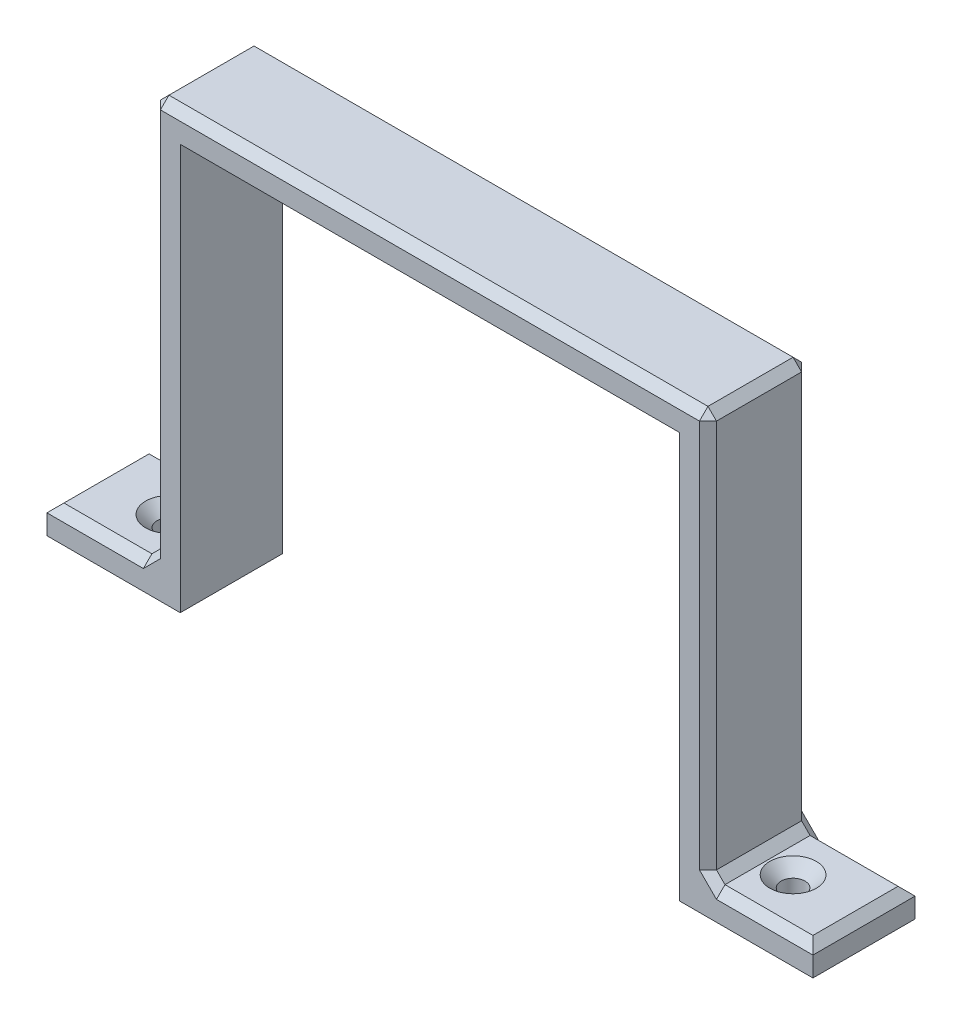
SolidWorks part; units mm, degrees
ref_plane "Front Plane" through (0, 0, 0) normal (0, 0, 1) x (1, 0, 0)
ref_plane "Top Plane" through (0, 0, 0) normal (0, 1, 0) x (1, 0, 0)
ref_plane "Right Plane" through (0, 0, 0) normal (1, 0, 0) x (0, 0, -1)
sketch "Sketch1" plane through (0, 0, 0) normal (0, 0, 1) x (1, 0, 0)
  line L0 (0, 48.7073) -> (0, -14.6895) construction
  line L1 (44, -27.85) -> (44, 43.65)
  line L2 (56.3161, -27.85) -> (55.25, -27.85) construction
  line L3 (44, 43.65) -> (-44, 43.65)
  line L4 (-49, 48.65) -> (49, 48.65)
  line L5 (49, 48.65) -> (49, -22.85)
  line L6 (49, -22.85) -> (67.5, -22.85)
  line L7 (67.5, -22.85) -> (67.5, -27.85)
  line L9 (67.5, -27.85) -> (44, -27.85)
  line L10 (49, -22.85) -> (49, -27.85) construction
  line L11 (0, 48.65) -> (0, 43.65) construction
  line L12 (-49, -22.85) -> (-49, -27.85) construction
  line L13 (-67.5, -27.85) -> (-44, -27.85)
  line L14 (-67.5, -22.85) -> (-67.5, -27.85)
  line L15 (-49, -22.85) -> (-67.5, -22.85)
  line L16 (-49, 48.65) -> (-49, -22.85)
  line L17 (-44, -27.85) -> (-44, 43.65)
  dimension "D1" = 71.5
  dimension "D2" = 44
  dimension "D3" = 5
  dimension "D4" = 5
  dimension "D5" = 135
  dimension "D6" = 5
extrude "Boss-Extrude1" add sketch "Sketch1" along normal mid plane 18
sketch "Sketch2" plane through (0, -27.85, 0) normal (0, -1, 0) x (1, 0, 0)
  line L0 (0, 8.47) -> (0, -7.1138) construction
  circle A0 centre (55, 0) radius 2.1
  circle A1 centre (-55, 0) radius 2.1
  dimension "D1" = 4.2
extrude "Cut-Extrude1" cut sketch "Sketch2" against normal mid plane 18
chamfer "Chamfer1" distance 2 angle 45 2 edges at (-52.9, -22.85, 0) (55, -22.85, -2.1)
chamfer "Chamfer2" distance 1.5 angle 45 16 edges at (49, 48.65, 0) (0, 48.65, 9) (-49, 48.65, 0) (0, 48.65, -9) (-49, 12.9, 9) (-49, 12.9, -9) (-49, -22.85, 0) (-58.25, -22.85, 9) (-67.5, -22.85, 0) (-58.25, -22.85, -9) (49, 12.9, 9) (49, 12.9, -9) (67.5, -22.85, 0) (58.25, -22.85, 9) (49, -22.85, 0) (58.25, -22.85, -9)
